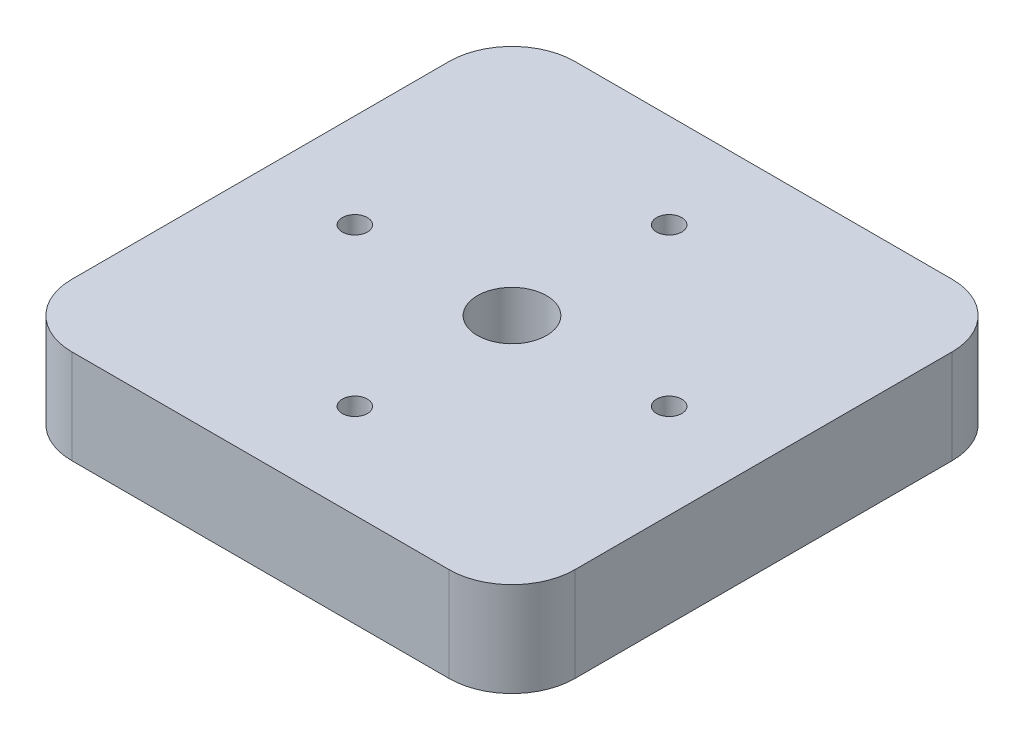
SolidWorks part; units mm, degrees
material "Cedar"
ref_plane "Plan de face" through (0, 0, 0) normal (0, 0, 1) x (1, 0, 0)
ref_plane "Plan de dessus" through (0, 0, 0) normal (0, 1, 0) x (1, 0, 0)
ref_plane "Plan de droite" through (0, 0, 0) normal (1, 0, 0) x (0, 0, -1)
sketch "Sketch1" plane through (0, 0, 0) normal (0, 1, 0) x (1, 0, 0)
  line L1 (-30, 40) -> (30, 40)
  line L2 (-40, 30) -> (-40, -30)
  line L3 (-30, -40) -> (30, -40)
  line L4 (40, 30) -> (40, -30)
  line L5 (-40, 40) -> (40, -40) construction
  line L6 (-40, -40) -> (40, 40) construction
  arc A0 (-40, -30) -> (-30, -40) centre (-30, -30) ccw
  arc A1 (30, -40) -> (40, -30) centre (30, -30) ccw
  arc A2 (30, 40) -> (40, 30) centre (30, 30) cw
  arc A3 (-30, 40) -> (-40, 30) centre (-30, 30) ccw
  circle A4 centre (0, 0) radius 7
  circle A5 centre (0, 25) radius 2
  circle A6 centre (0, -25) radius 2
  circle A7 centre (-25, 0) radius 2
  circle A8 centre (25, 0) radius 2
  point P0 (0, 0)
  point P28 (0, 0)
  point P29 (0, 0)
  point P30 (0, 0)
  point P32 (1.5345, 1.5345)
  dimension "D2" = 10
  dimension "D3" = 14
  dimension "D7" = 25
  dimension "D8" = 4
  dimension "D1" = 80
  dimension "D4" = 25
  dimension "D5" = 25
  dimension "D6" = 25
extrude "Boss-Extrude1" add sketch "Sketch1" along normal blind 15
sketch "Sketch2" plane through (0, 15, 0) normal (0, 1, 0) x (1, 0, 0)
  circle A0 centre (0, 0) radius 7 construction
  circle A1 centre (0, 0) radius 7
  circle A2 centre (0, 0) radius 5.5
  dimension "D1" = 11
extrude "Boss-Extrude2" add sketch "Sketch2" against normal blind 8
